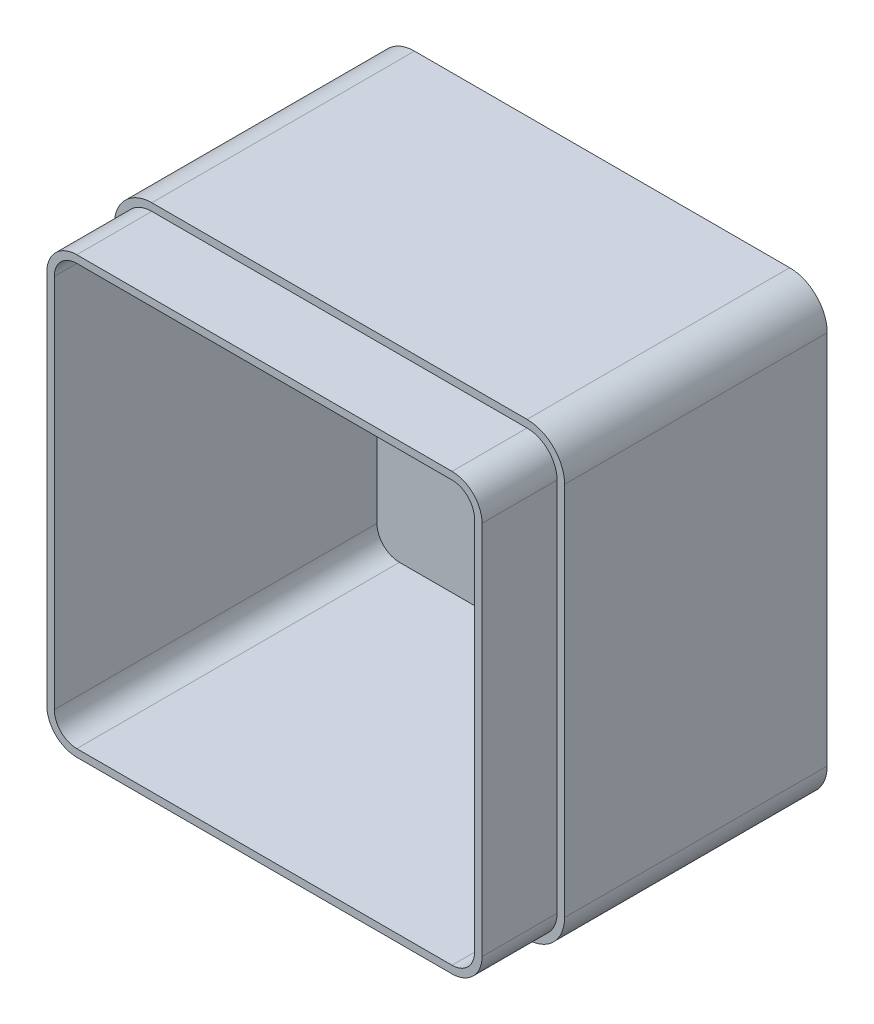
SolidWorks part; units mm, degrees
ref_plane "Front" through (0, 0, 0) normal (0, 0, 1) x (1, 0, 0)
ref_plane "Top" through (0, 0, 0) normal (0, 1, 0) x (1, 0, 0)
ref_plane "Right" through (0, 0, 0) normal (1, 0, 0) x (0, 0, -1)
sketch "Эскиз1" plane through (0, 0, 0) normal (0, 0, 1) x (1, 0, 0)
  line L1 (0, 0) -> (120, 0)
  line L2 (0, 0) -> (0, 120)
  line L3 (0, 120) -> (120, 120)
  line L4 (120, 0) -> (120, 120)
  dimension "D1" = 120
  dimension "D2" = 120
extrude "Бобышка-Вытянуть1" add sketch "Эскиз1" along normal blind 90
fillet "Скругление1" radius 10 4 edges at (0, 0, 45) (120, 0, 45) (120, 120, 45) (0, 120, 45)
shell "Оболочка1" thickness 4
sketch "Эскиз2" plane through (0, 0, 90) normal (0, 0, 1) x (1, 0, 0)
  line L0 (2, 110) -> (2, 10)
  line L1 (10, 2) -> (110, 2)
  line L2 (118, 10) -> (118, 110)
  line L3 (110, 118) -> (10, 118)
  line L4 (0, 110) -> (0, 10)
  line L5 (10, 0) -> (110, 0)
  line L6 (120, 10) -> (120, 110)
  line L7 (110, 120) -> (10, 120)
  line L8 (0, 110) -> (0, 10)
  line L9 (10, 0) -> (110, 0)
  line L10 (120, 10) -> (120, 110)
  line L11 (110, 120) -> (10, 120)
  arc A0 (10, 118) -> (2, 110) centre (10, 110) ccw
  arc A1 (2, 10) -> (10, 2) centre (10, 10) ccw
  arc A2 (110, 2) -> (118, 10) centre (110, 10) ccw
  arc A3 (118, 110) -> (110, 118) centre (110, 110) ccw
  arc A4 (0, 10) -> (10, 0) centre (10, 10) ccw
  arc A5 (110, 0) -> (120, 10) centre (110, 10) ccw
  arc A6 (120, 110) -> (110, 120) centre (110, 110) ccw
  arc A7 (10, 120) -> (0, 110) centre (10, 110) ccw
  arc A8 (0, 10) -> (10, 0) centre (10, 10) ccw
  arc A9 (110, 0) -> (120, 10) centre (110, 10) ccw
  arc A10 (120, 110) -> (110, 120) centre (110, 110) ccw
  arc A11 (10, 120) -> (0, 110) centre (10, 110) ccw
  dimension "D1" = 0
  dimension "D2" = 2
extrude "Вырез-Вытянуть1" cut sketch "Эскиз2" against normal blind 20
